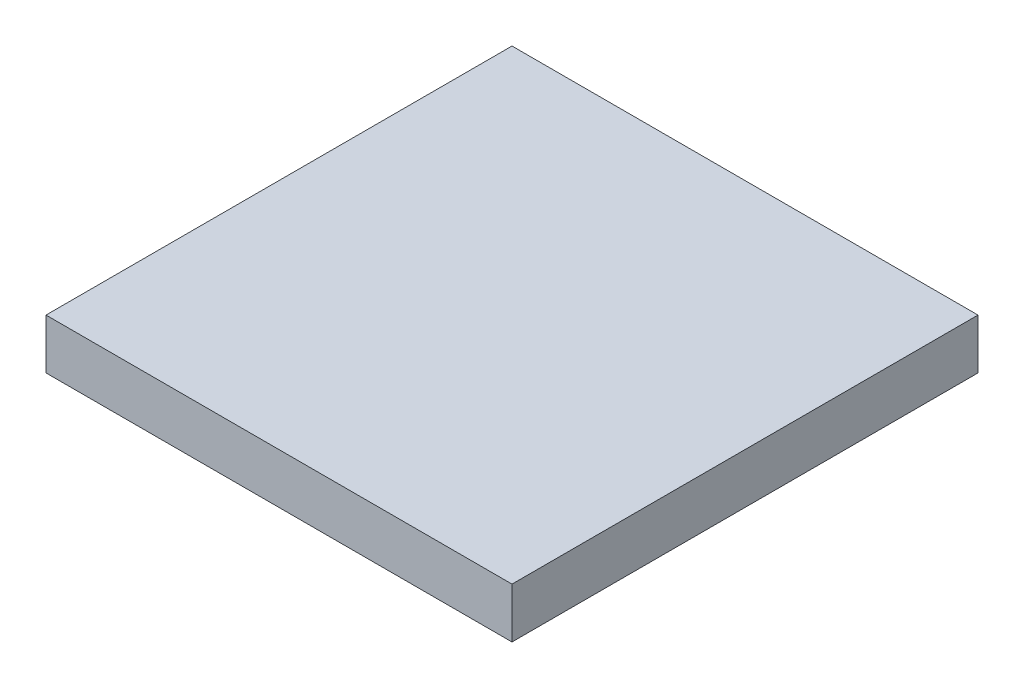
SolidWorks part; units mm, degrees
material "Cast Alloy Steel"
ref_plane "Front Plane" through (0, 0, 0) normal (0, 0, 1) x (1, 0, 0)
ref_plane "Top Plane" through (0, 0, 0) normal (0, 1, 0) x (1, 0, 0)
ref_plane "Right Plane" through (0, 0, 0) normal (1, 0, 0) x (0, 0, -1)
sketch "Sketch1" plane through (0, 0, 0) normal (0, 1, 0) x (1, 0, 0)
  line L0 (-2, 8.0804) -> (-2, -149.9196)
  line L1 (0, 6.0804) -> (154, 6.0804)
  line L2 (0, 6.0804) -> (0, -147.9196)
  line L3 (0, -147.9196) -> (154, -147.9196)
  line L4 (154, 6.0804) -> (154, -147.9196)
  line L5 (-2, -149.9196) -> (156, -149.9196)
  line L6 (156, 8.0804) -> (156, -149.9196)
  line L7 (-2, 8.0804) -> (156, 8.0804)
  dimension "D1" = 154
  dimension "D2" = 154
  dimension "D3" = 2
extrude "Boss-Extrude1" add sketch "Sketch1" along normal blind 15
ref_plane "Plane1" through (-2, 15, 149.9196) normal (1, 0, 0) x (0, 0, -1)
sketch "Sketch3" plane through (0, 15, 0) normal (0, 1, 0) x (1, 0, 0)
  line L1 (-2, 8.0804) -> (156, 8.0804)
  line L2 (-2, 8.0804) -> (-2, -149.9196)
  line L3 (-2, -149.9196) -> (156, -149.9196)
  line L4 (156, 8.0804) -> (156, -149.9196)
extrude "Boss-Extrude2" add sketch "Sketch3" along normal blind 2
sketch "Sketch4" plane through (0, 17, 0) normal (0, 1, 0) x (1, 0, 0)
  line L0 (77, 8.0804) -> (77, -149.9196) construction
  line L1 (156, 8.0804) -> (-2, 8.0804) construction
  line L2 (-2, -149.9196) -> (156, -149.9196) construction
  circle A0 centre (77, -70.9196) radius 4
